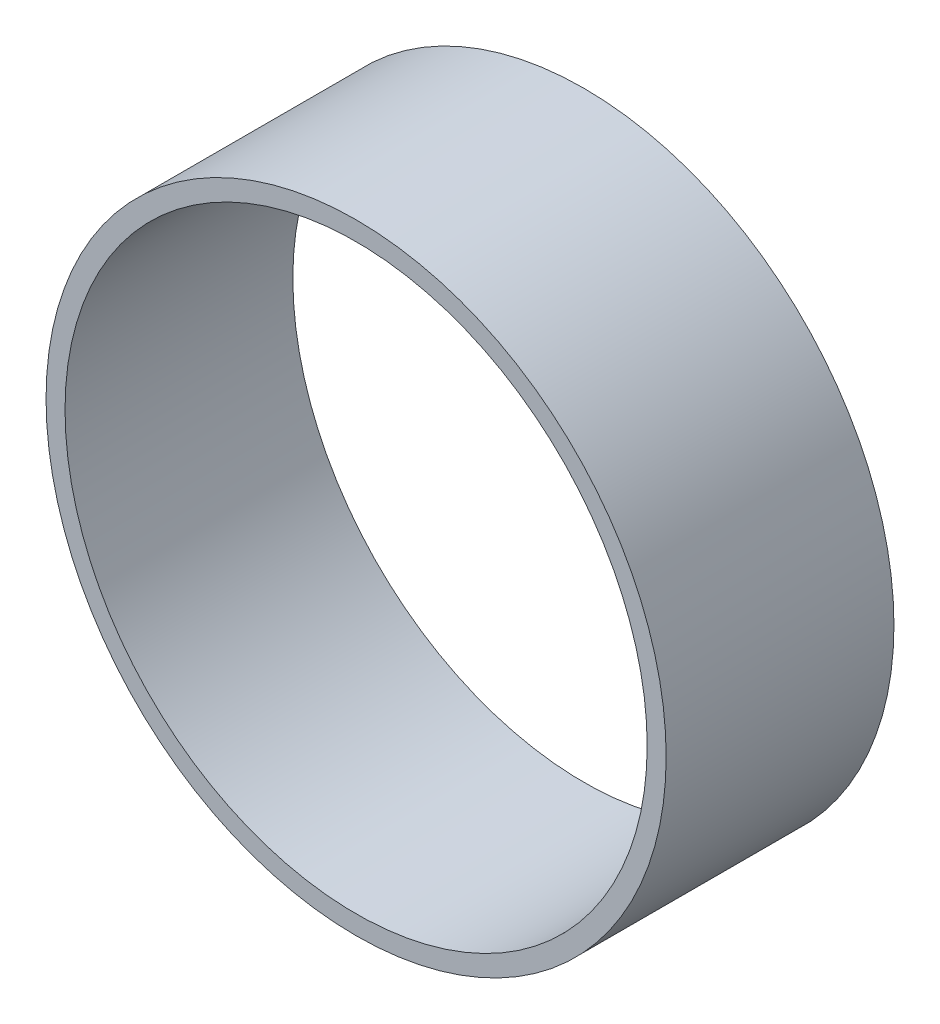
SolidWorks part; units mm, degrees
material "AISI 316 Stainless Steel Sheet (SS)"
ref_plane "Front Plane" through (0, 0, 0) normal (0, 0, 1) x (1, 0, 0)
ref_plane "Top Plane" through (0, 0, 0) normal (0, 1, 0) x (1, 0, 0)
ref_plane "Right Plane" through (0, 0, 0) normal (1, 0, 0) x (0, 0, -1)
sketch "Sketch1" plane through (0, 0, 0) normal (0, 0, 1) x (1, 0, 0)
  circle A0 centre (0, 0) radius 122.5
  circle A1 centre (0, 0) radius 115
  dimension "D1" = 245
  dimension "D2" = 230
extrude "Boss-Extrude1" add sketch "Sketch1" along normal blind 90
